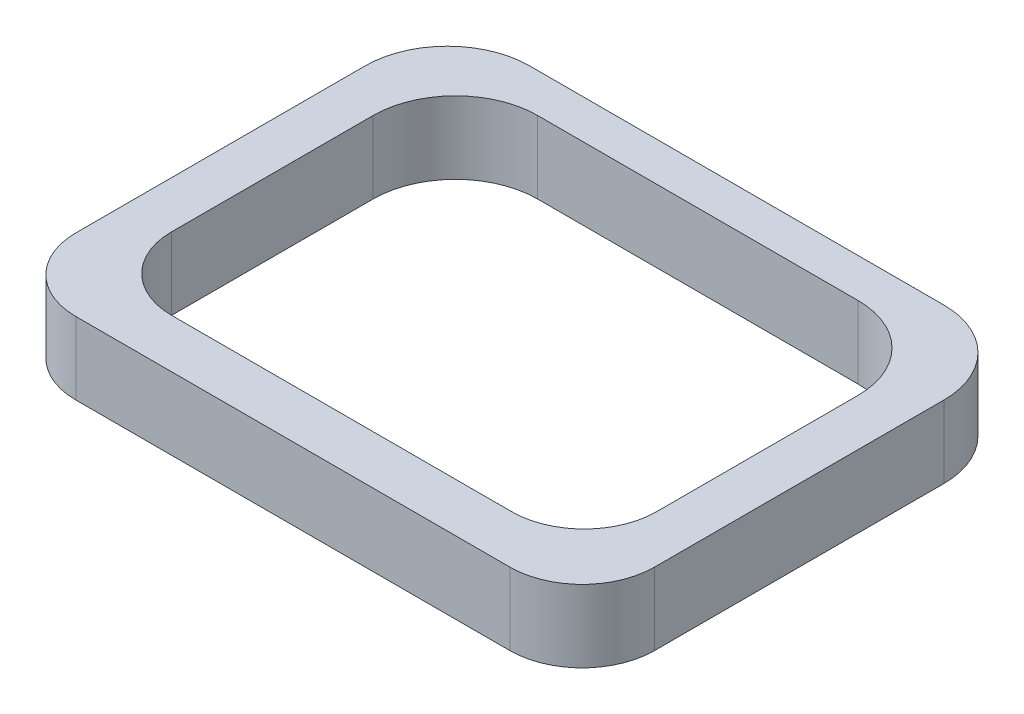
SolidWorks part; units mm, degrees
ref_plane "Front Plane" through (0, 0, 0) normal (0, 0, 1) x (1, 0, 0)
ref_plane "Top Plane" through (0, 0, 0) normal (0, 1, 0) x (1, 0, 0)
ref_plane "Right Plane" through (0, 0, 0) normal (1, 0, 0) x (0, 0, -1)
sketch "Sketch1" plane through (0, 0, 0) normal (0, 1, 0) x (1, 0, 0)
  line L0 (-85.9, 92.05) -> (85.9, 92.05)
  line L5 (120, 0) -> (-120, 0) construction
  line L6 (0, 92.05) -> (0, -92.05) construction
  line L11 (-120, 57.95) -> (-120, -62.05)
  line L12 (-90, -92.05) -> (90, -92.05)
  line L13 (120, 57.95) -> (120, -62.05)
  line L14 (-66.4277, 75.8803) -> (66.4277, 75.8803)
  line L15 (-100.5277, 41.7803) -> (-100.5277, -41.7803)
  line L16 (-70.5277, -71.7803) -> (70.5277, -71.7803)
  line L17 (100.5277, 41.7803) -> (100.5277, -41.7803)
  line L28 (-100.5277, 0) -> (100.5277, 0) construction
  line L29 (0, 75.8803) -> (0, -71.7803) construction
  arc A0 (85.9, 92.05) -> (120, 57.95) centre (85.9, 57.95) cw
  arc A1 (-85.9, 92.05) -> (-120, 57.95) centre (-85.9, 57.95) ccw
  arc A2 (-120, -62.05) -> (-90, -92.05) centre (-90, -62.05) ccw
  arc A3 (90, -92.05) -> (120, -62.05) centre (90, -62.05) ccw
  arc A4 (66.4277, 75.8803) -> (100.5277, 41.7803) centre (66.4277, 41.7803) cw
  arc A5 (-66.4277, 75.8803) -> (-100.5277, 41.7803) centre (-66.4277, 41.7803) ccw
  arc A6 (-100.5277, -41.7803) -> (-70.5277, -71.7803) centre (-70.5277, -41.7803) ccw
  arc A7 (70.5277, -71.7803) -> (100.5277, -41.7803) centre (70.5277, -41.7803) ccw
  point P0 (0, 0)
  point P18 (0, 0)
  point P53 (0, 0)
  point P54 (0, 0)
  point P55 (0, 0)
  dimension "D3" = 30
  dimension "D4" = 34.1
  dimension "D12" = 30
  dimension "D1" = 120
  dimension "D2" = 180
  dimension "D9" = 83.5607
  dimension "D10" = 132.8553
  dimension "D11" = 141.0553
extrude "Boss-Extrude2" add sketch "Sketch1" along normal blind 30
